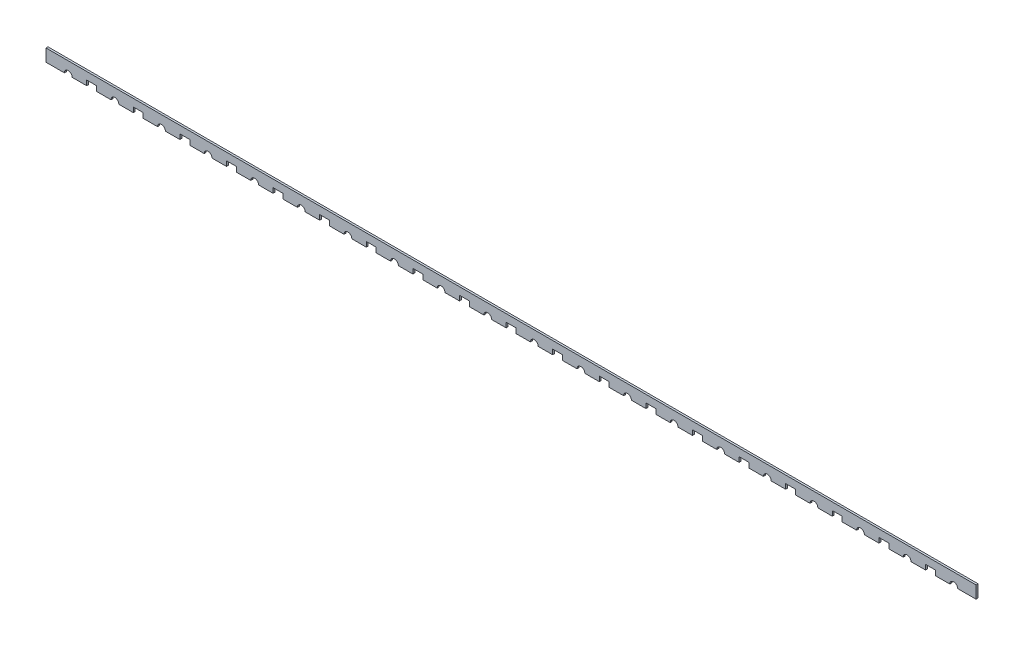
SolidWorks part; units mm, degrees
ref_plane "Front Plane" through (0, 0, 0) normal (0, 0, 1) x (1, 0, 0)
ref_plane "Top Plane" through (0, 0, 0) normal (0, 1, 0) x (1, 0, 0)
ref_plane "Right Plane" through (0, 0, 0) normal (1, 0, 0) x (0, 0, -1)
sketch "Sketch1" plane through (0, 0, 0) normal (0, 0, 1) x (1, 0, 0)
  line L0 (0, -25) -> (-155.5003, -25) construction
  line L1 (0, 0) -> (-131.1, 0)
  line L2 (0, 0) -> (0, -25)
  line L3 (0, -25) -> (-37.1, -25)
  line L4 (-146.9, -25) -> (-176, -25)
  line L5 (-102, -7) -> (-102, -45) construction
  line L6 (-102, -25) -> (-131.1, -25)
  line L7 (-102, -25) -> (-102, -15)
  line L8 (-102, -15) -> (-82, -15)
  line L9 (-82, -25) -> (-82, -15)
  line L10 (-52.9, -25) -> (-82, -25)
  line L11 (-176, -25) -> (-176, -15)
  line L12 (-196, -15) -> (-176, -15)
  line L13 (-196, -25) -> (-196, -15)
  line L14 (-196, -25) -> (-225.1, -25)
  line L15 (-240.9, -25) -> (-270, -25)
  line L16 (-270, -25) -> (-270, -15)
  line L17 (-290, -15) -> (-270, -15)
  line L18 (-290, -25) -> (-290, -15)
  line L19 (-290, -25) -> (-319.1, -25)
  line L20 (-334.9, -25) -> (-364, -25)
  line L21 (-364, -25) -> (-364, -15)
  line L22 (-384, -15) -> (-364, -15)
  line L23 (-384, -25) -> (-384, -15)
  line L24 (-384, -25) -> (-413.1, -25)
  line L25 (-428.9, -25) -> (-458, -25)
  line L26 (-458, -25) -> (-458, -15)
  line L27 (-478, -15) -> (-458, -15)
  line L28 (-478, -25) -> (-478, -15)
  line L29 (-478, -25) -> (-507.1, -25)
  line L30 (-522.9, -25) -> (-552, -25)
  line L31 (-552, -25) -> (-552, -15)
  line L32 (-572, -15) -> (-552, -15)
  line L33 (-572, -25) -> (-572, -15)
  line L34 (-572, -25) -> (-601.1, -25)
  line L35 (-616.9, -25) -> (-646, -25)
  line L36 (-646, -25) -> (-646, -15)
  line L37 (-666, -15) -> (-646, -15)
  line L38 (-666, -25) -> (-666, -15)
  line L39 (-666, -25) -> (-695.1, -25)
  line L40 (-710.9, -25) -> (-740, -25)
  line L41 (-740, -25) -> (-740, -15)
  line L42 (-760, -15) -> (-740, -15)
  line L43 (-760, -25) -> (-760, -15)
  line L44 (-760, -25) -> (-789.1, -25)
  line L45 (-804.9, -25) -> (-834, -25)
  line L46 (-834, -25) -> (-834, -15)
  line L47 (-854, -15) -> (-834, -15)
  line L48 (-854, -25) -> (-854, -15)
  line L49 (-854, -25) -> (-883.1, -25)
  line L50 (-898.9, -25) -> (-928, -25)
  line L51 (-928, -25) -> (-928, -15)
  line L52 (-948, -15) -> (-928, -15)
  line L53 (-948, -25) -> (-948, -15)
  line L54 (-948, -25) -> (-977.1, -25)
  line L55 (-992.9, -25) -> (-1022, -25)
  line L56 (-1022, -25) -> (-1022, -15)
  line L57 (-1042, -15) -> (-1022, -15)
  line L58 (-1042, -25) -> (-1042, -15)
  line L59 (-1042, -25) -> (-1071.1, -25)
  line L60 (-1086.9, -25) -> (-1116, -25)
  line L61 (-1116, -25) -> (-1116, -15)
  line L62 (-1136, -15) -> (-1116, -15)
  line L63 (-1136, -25) -> (-1136, -15)
  line L64 (-1136, -25) -> (-1165.1, -25)
  line L65 (-1180.9, -25) -> (-1210, -25)
  line L66 (-1210, -25) -> (-1210, -15)
  line L67 (-1230, -15) -> (-1210, -15)
  line L68 (-1230, -25) -> (-1230, -15)
  line L69 (-1230, -25) -> (-1259.1, -25)
  line L70 (-1274.9, -25) -> (-1304, -25)
  line L71 (-1304, -25) -> (-1304, -15)
  line L72 (-1324, -15) -> (-1304, -15)
  line L73 (-1324, -25) -> (-1324, -15)
  line L74 (-1324, -25) -> (-1353.1, -25)
  line L75 (-1368.9, -25) -> (-1398, -25)
  line L76 (-1398, -25) -> (-1398, -15)
  line L77 (-1418, -15) -> (-1398, -15)
  line L78 (-1418, -25) -> (-1418, -15)
  line L79 (-1418, -25) -> (-1447.1, -25)
  line L80 (-1462.9, -25) -> (-1492, -25)
  line L81 (-1492, -25) -> (-1492, -15)
  line L82 (-1512, -15) -> (-1492, -15)
  line L83 (-1512, -25) -> (-1512, -15)
  line L84 (-1512, -25) -> (-1541.1, -25)
  line L85 (-1556.9, -25) -> (-1586, -25)
  line L86 (-1586, -25) -> (-1586, -15)
  line L87 (-1606, -15) -> (-1586, -15)
  line L88 (-1606, -25) -> (-1606, -15)
  line L89 (-1606, -25) -> (-1635.1, -25)
  line L90 (-1650.9, -25) -> (-1680, -25)
  line L91 (-1680, -25) -> (-1680, -15)
  line L92 (-1700, -15) -> (-1680, -15)
  line L93 (-1700, -25) -> (-1700, -15)
  line L94 (-1700, -25) -> (-1729.1, -25)
  line L95 (-1744.9, -25) -> (-1774, -25)
  line L96 (-1774, -25) -> (-1774, -15)
  line L97 (-1794, -15) -> (-1774, -15)
  line L98 (-1794, -25) -> (-1794, -15)
  line L99 (-1794, -25) -> (-1823.1, -25)
  line L100 (-1838.9, -25) -> (-1868, -25)
  line L101 (-1868, -25) -> (-1876, -25)
  line L102 (-1876, -25) -> (-1876, 0)
  line L103 (-37, 0) -> (-1897.553, 0) construction
  line L104 (-1876, 0) -> (-131.1, 0)
  line L105 (-1868, -25) -> (-1868, -15) [skipped]
  line L106 (-1888, -15) -> (-1868, -15) [skipped]
  line L107 (-1888, -25) -> (-1888, -15) [skipped]
  line L108 (-1888, -25) -> (-1917.1, -25) [skipped]
  circle A0 centre (-139, -25) radius 7.9 construction
  circle A1 centre (-45, -25) radius 7.9 construction
  arc A2 (-37.1, -25) -> (-52.9, -25) centre (-45, -25) ccw
  arc A3 (-131.1, -25) -> (-146.9, -25) centre (-139, -25) ccw
  arc A4 (-225.1, -25) -> (-240.9, -25) centre (-233, -25) ccw
  arc A5 (-319.1, -25) -> (-334.9, -25) centre (-327, -25) ccw
  arc A6 (-413.1, -25) -> (-428.9, -25) centre (-421, -25) ccw
  arc A7 (-507.1, -25) -> (-522.9, -25) centre (-515, -25) ccw
  arc A8 (-601.1, -25) -> (-616.9, -25) centre (-609, -25) ccw
  arc A9 (-695.1, -25) -> (-710.9, -25) centre (-703, -25) ccw
  arc A10 (-789.1, -25) -> (-804.9, -25) centre (-797, -25) ccw
  arc A11 (-883.1, -25) -> (-898.9, -25) centre (-891, -25) ccw
  arc A12 (-977.1, -25) -> (-992.9, -25) centre (-985, -25) ccw
  arc A13 (-1071.1, -25) -> (-1086.9, -25) centre (-1079, -25) ccw
  arc A14 (-1165.1, -25) -> (-1180.9, -25) centre (-1173, -25) ccw
  arc A15 (-1259.1, -25) -> (-1274.9, -25) centre (-1267, -25) ccw
  arc A16 (-1353.1, -25) -> (-1368.9, -25) centre (-1361, -25) ccw
  arc A17 (-1447.1, -25) -> (-1462.9, -25) centre (-1455, -25) ccw
  arc A18 (-1541.1, -25) -> (-1556.9, -25) centre (-1549, -25) ccw
  arc A19 (-1635.1, -25) -> (-1650.9, -25) centre (-1643, -25) ccw
  arc A20 (-1729.1, -25) -> (-1744.9, -25) centre (-1737, -25) ccw
  arc A21 (-1823.1, -25) -> (-1838.9, -25) centre (-1831, -25) ccw
  dimension "D1" = 20
extrude "Boss-Extrude1" add sketch "Sketch1" along normal blind 4
